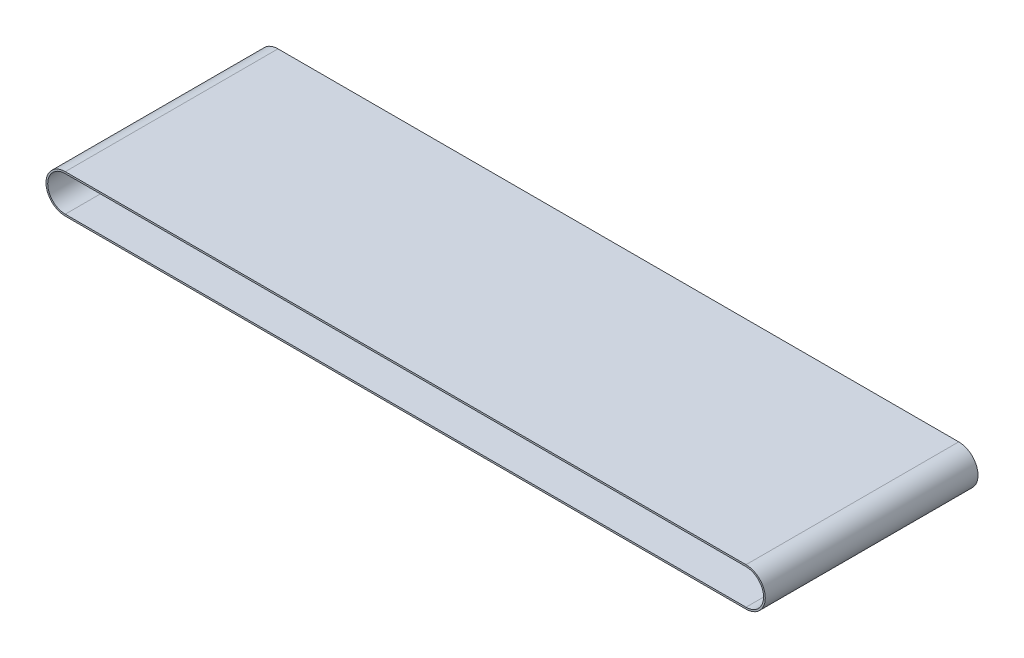
SolidWorks part; units mm, degrees
material "Rubber"
ref_plane "Front Plane" through (0, 0, 0) normal (0, 0, 1) x (1, 0, 0)
ref_plane "Top Plane" through (0, 0, 0) normal (0, 1, 0) x (1, 0, 0)
ref_plane "Right Plane" through (0, 0, 0) normal (1, 0, 0) x (0, 0, -1)
sketch "Sketch1" plane through (0, 0, 0) normal (0, 0, 1) x (1, 0, 0)
  line L0 (0, 0) -> (800, 0) construction
  line L1 (0, 22.6396) -> (800, 22.6396)
  line L2 (0, -22.6396) -> (800, -22.6396)
  line L3 (0, 20.6396) -> (800, 20.6396)
  line L4 (0, -20.6396) -> (800, -20.6396)
  arc A0 (0, 22.6396) -> (0, -22.6396) centre (0, 0) ccw
  arc A1 (800, -22.6396) -> (800, 22.6396) centre (800, 0) ccw
  arc A2 (800, -20.6396) -> (800, 20.6396) centre (800, 0) ccw
  arc A3 (0, 20.6396) -> (0, -20.6396) centre (0, 0) ccw
  point P3 (400, 0)
  dimension "D2" = 800
  dimension "D1" = 2
extrude "Boss-Extrude1" add sketch "Sketch1" along normal blind 250
